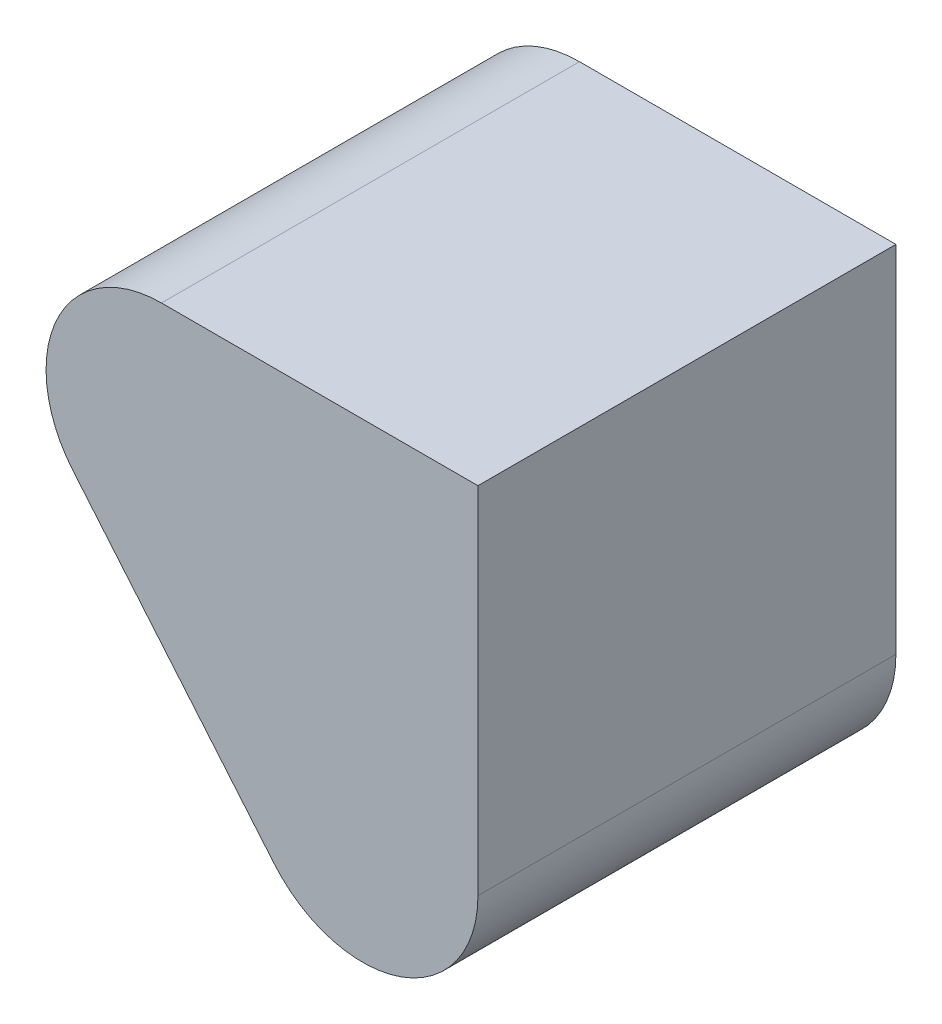
SolidWorks part; units mm, degrees
ref_plane "前视基准面" through (0, 0, 0) normal (0, 0, 1) x (1, 0, 0)
ref_plane "上视基准面" through (0, 0, 0) normal (0, 1, 0) x (1, 0, 0)
ref_plane "右视基准面" through (0, 0, 0) normal (1, 0, 0) x (0, 0, -1)
other "Configuration Table"
sketch "草图1" plane through (0, 0, 0) normal (0, 0, 1) x (1, 0, 0)
  line L0 (-8.4608, -7.0995) -> (-27.7034, 15.8329)
  line L3 (11.0448, 0) -> (11.0448, 33.9772)
  line L4 (11.0448, 33.9772) -> (-19.2426, 33.9772)
  line L5 (-19.2426, 22.9324) -> (0, 0) construction
  line L6 (0, 0) -> (34.0019, 0) construction
  arc A1 (-27.7034, 15.8329) -> (-19.2426, 33.9772) centre (-19.2426, 22.9324) cw
  arc A3 (-8.4608, -7.0995) -> (11.0448, 0) centre (0, 0) ccw
  dimension "D1" = 130
extrude "凸台-拉伸1" add sketch "草图1" along normal blind 40
